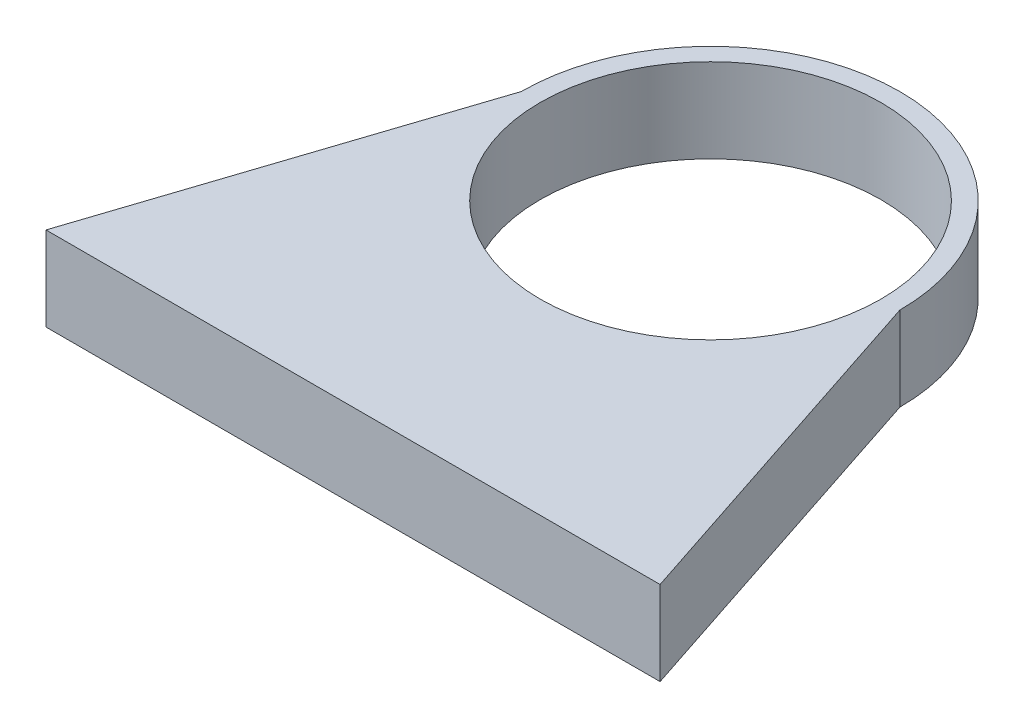
SolidWorks part; units mm, degrees
ref_plane "Front Plane" through (0, 0, 0) normal (0, 0, 1) x (1, 0, 0)
ref_plane "Top Plane" through (0, 0, 0) normal (0, 1, 0) x (1, 0, 0)
ref_plane "Right Plane" through (0, 0, 0) normal (1, 0, 0) x (0, 0, -1)
sketch "Sketch1" plane through (0, 0, 0) normal (0, 1, 0) x (1, 0, 0)
  line L0 (-22.5, 0) -> (22.5, 0) construction
  line L1 (0, 0) -> (0, -42.5) construction
  line L2 (-36.5, -42.5) -> (36.5, -42.5)
  line L3 (-36.5, -42.5) -> (-22.5, 0)
  line L4 (22.5, 0) -> (36.5, -42.5)
  circle A0 centre (0, 0) radius 20.25
  arc A1 (22.5, 0) -> (-22.5, 0) centre (0, 0) ccw
  point P7 (0, 0)
  point P11 (0, -42.5)
  point P12 (0, 0)
  dimension "D1" = 40.5
  dimension "D2" = 45
  dimension "D3" = 42.5
  dimension "D4" = 73
extrude "Boss-Extrude1" add sketch "Sketch1" along normal blind 10 contours A1 L3 L2 L4 | A0
